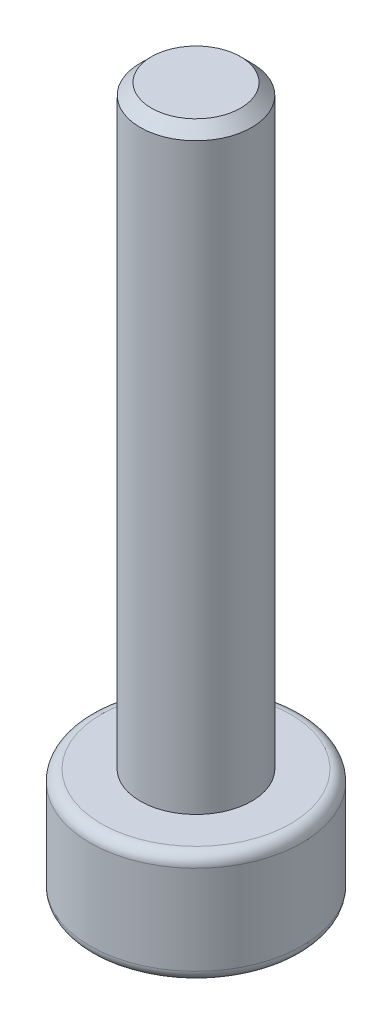
SolidWorks part; units mm, degrees
material "AISI 304"
ref_plane "前视基准面" through (0, 0, 0) normal (0, 0, 1) x (1, 0, 0)
ref_plane "上视基准面" through (0, 0, 0) normal (0, 1, 0) x (1, 0, 0)
ref_plane "右视基准面" through (0, 0, 0) normal (1, 0, 0) x (0, 0, -1)
sketch "草图1" plane through (0, 0, 0) normal (0, 1, 0) x (1, 0, 0)
  circle A0 centre (0, 0) radius 2.85
  dimension "D1" = 5.7
extrude "凸台-拉伸1" add sketch "草图1" along normal blind 3
sketch "草图2" plane through (0, 3, 0) normal (0, 1, 0) x (1, 0, 0)
  circle A0 centre (0, 0) radius 1.5
  dimension "D1" = 3
extrude "凸台-拉伸2" add sketch "草图2" along normal blind 16
sketch "草图3" plane through (0, 0, 0) normal (0, -1, 0) x (1, 0, 0)
  circle A0 centre (0, 0) radius 1.29
  dimension "D1" = 2.58
extrude "切除-拉伸1" cut sketch "草图3" against normal blind 1.3
fillet "圆角1" radius 0.3 2 edges at (0, 3, 2.85) (0, 0, 2.85)
chamfer "倒角1" distance 0.3 angle 45 1 edges at (0, 19, 1.5)
chamfer "倒角2" distance 0.15 angle 45 1 edges at (0, 0, -1.29)
